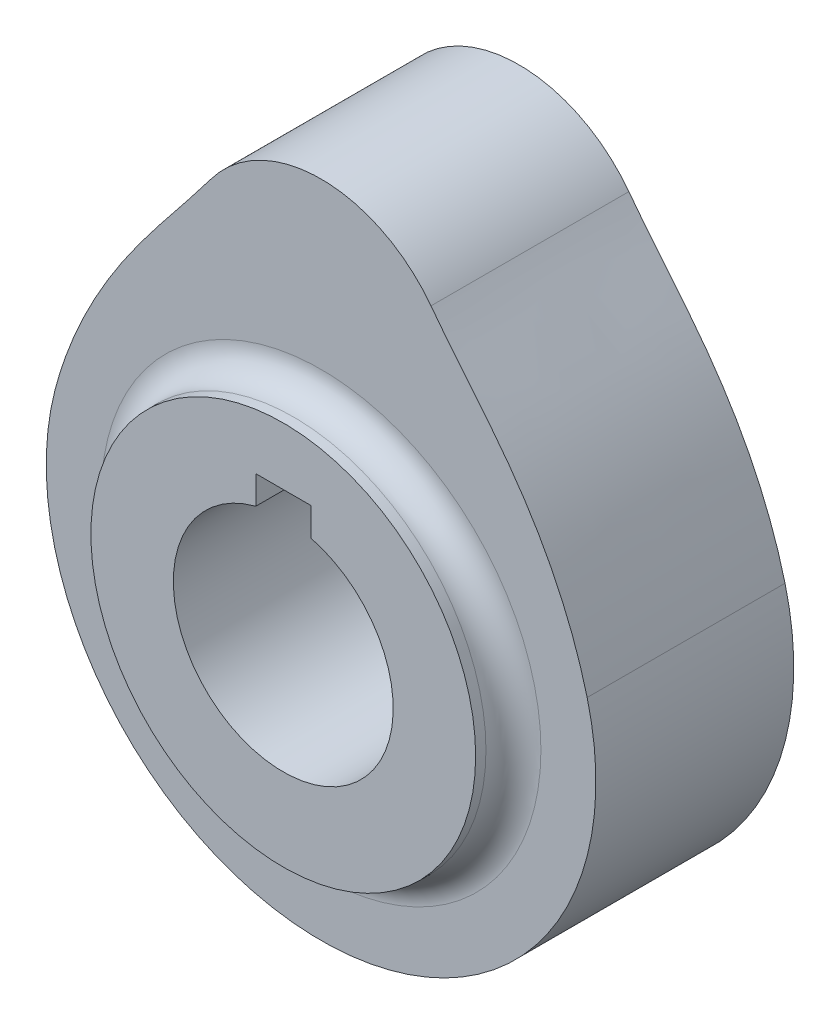
SolidWorks part; units mm, degrees
ref_plane "Front Plane" through (0, 0, 0) normal (0, 0, 1) x (1, 0, 0)
ref_plane "Top Plane" through (0, 0, 0) normal (0, 1, 0) x (1, 0, 0)
ref_plane "Right Plane" through (0, 0, 0) normal (1, 0, 0) x (0, 0, -1)
sketch "Sketch1" plane through (0, 0, 0) normal (0, 0, 1) x (1, 0, 0)
  line L2 (0, 0) -> (0, 18) construction
  arc A0 (8, 24) -> (-8, 24) centre (0, 18) ccw
  arc A1 (19.3649, 5) -> (-19.3649, 5) centre (0, 0) cw
  spline S0 degree 3 poles (-8, 24) (-9.8858, 21.4856) (-14.7683, 15.8742) (-18.2976, 9.1337) (-19.3649, 5) knots 0 0 0 0 0.425985 1 1 1 1
  spline S1 degree 3 poles (19.3649, 5) (18.2288, 9.4002) (14.8353, 16.0327) (9.9746, 21.3672) (8, 24) knots 0 0 0 0 0.579854 1 1 1 1
  dimension "D2" = 10
  dimension "D3" = 20
  dimension "D1" = 18
  dimension "D4" = 24
  dimension "D5" = 24
  dimension "D6" = 8
  dimension "D7" = 13.8
  dimension "D8" = 13.8
  dimension "D9" = 16.6555
  dimension "D10" = 8
  dimension "D11" = 16.5
  dimension "D12" = 5
  dimension "D13" = 5
extrude "CamBody" add sketch "Sketch1" along normal blind 14.4
sketch "Sketch2" plane through (0, 0, 14.4) normal (0, 0, 1) x (1, 0, 0)
  circle A0 centre (0, 0) radius 14
  dimension "D1" = 28
extrude "Boss" add sketch "Sketch2" along normal blind 2.75 and the other way blind 17.25
fillet "BossFillets" radius 2 2 edges at (14, 0, 0) (14, 0, 14.4)
sketch "Sketch3" plane through (0, 0, 17.15) normal (0, 0, 1) x (1, 0, 0)
  circle A0 centre (0, 0) radius 8
  dimension "D1" = 16
extrude "Bore" cut sketch "Sketch3" against normal through all
sketch "Sketch4" plane through (0, 0, 17.15) normal (0, 0, 1) x (1, 0, 0)
  line L1 (-2, 4.8) -> (2, 4.8)
  line L2 (-2, 4.8) -> (-2, 9.8)
  line L3 (-2, 9.8) -> (2, 9.8)
  line L4 (2, 4.8) -> (2, 9.8)
  dimension "D1" = 9.8
  dimension "D2" = 5
  dimension "D3" = 4
  dimension "D4" = 2
extrude "KeySlot" cut sketch "Sketch4" against normal through all
